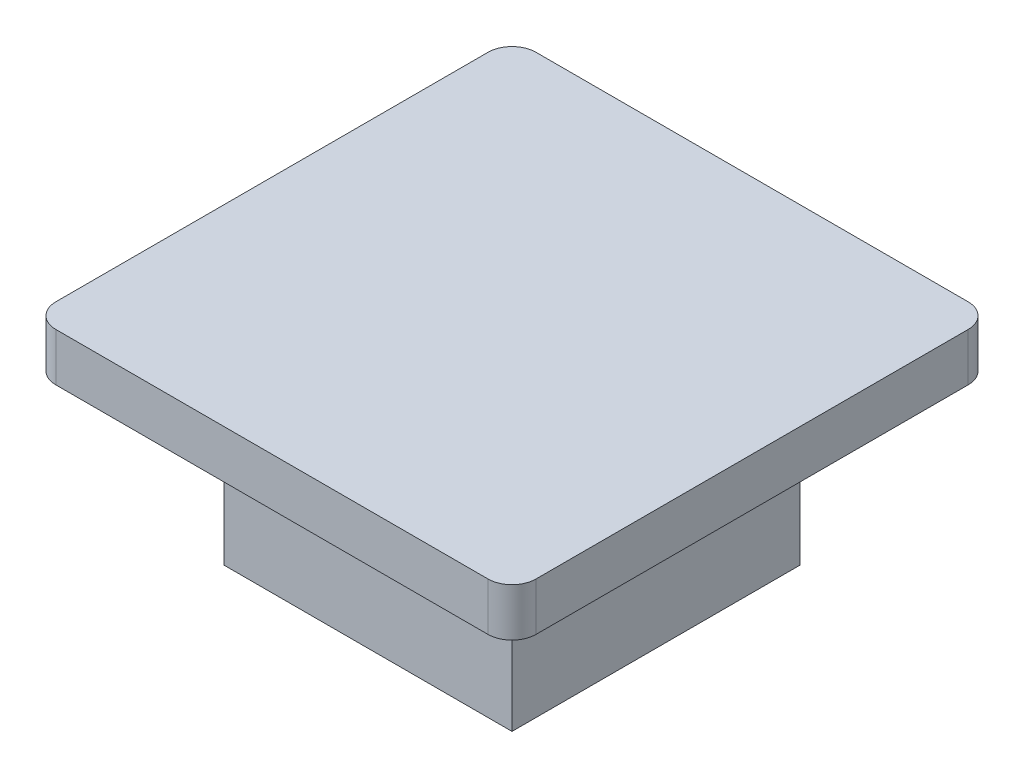
SolidWorks part; units mm, degrees
ref_plane "Front Plane" through (0, 0, 0) normal (0, 0, 1) x (1, 0, 0)
ref_plane "Top Plane" through (0, 0, 0) normal (0, 1, 0) x (1, 0, 0)
ref_plane "Right Plane" through (0, 0, 0) normal (1, 0, 0) x (0, 0, -1)
sketch "Sketch1" plane through (0, 0, 0) normal (0, 1, 0) x (1, 0, 0)
  line L1 (-100, -100) -> (100, -100)
  line L2 (-100, -100) -> (-100, 100)
  line L3 (-100, 100) -> (100, 100)
  line L4 (100, -100) -> (100, 100)
  line L5 (-100, -100) -> (100, 100) construction
  line L6 (-100, 100) -> (100, -100) construction
  point P0 (0, 0)
  dimension "D1" = 200
  dimension "D2" = 200
extrude "Boss-Extrude1" add sketch "Sketch1" along normal blind 20
sketch "Sketch3" plane through (0, 0, 0) normal (0, -1, 0) x (1, 0, 0)
  line L6 (-60, -60) -> (60, -60)
  line L7 (-60, -60) -> (-60, 60)
  line L8 (-60, 60) -> (60, 60)
  line L9 (60, -60) -> (60, 60)
  line L10 (-60, -60) -> (60, 60) construction
  line L11 (-60, 60) -> (60, -60) construction
  point P0 (0, 0)
  dimension "D1" = 120
  dimension "D2" = 120
extrude "Boss-Extrude2" add sketch "Sketch3" along normal blind 70
sketch "Sketch4" plane through (0, -70, 0) normal (0, -1, 0) x (1, 0, 0)
  line L0 (-80, 0) -> (117.0668, 0) construction
  line L2 (3.6479, 28.9379) -> (30.9916, 10.335)
  line L3 (3.6479, -28.9379) -> (30.9916, -10.335)
  arc A0 (30.9916, -10.335) -> (30.9916, 10.335) centre (23.9604, 0) ccw
  arc A1 (3.6479, 28.9379) -> (3.6479, -28.9379) centre (-16.0396, 0) ccw
  dimension "D2" = 25
  dimension "D3" = 35
  dimension "D1" = 40
extrude "Cut-Extrude1" cut sketch "Sketch4" against normal blind 20
sketch "Sketch5" plane through (0, -50, 0) normal (0, -1, 0) x (1, 0, 0)
  circle A0 centre (-16.0396, 0) radius 16
  circle A1 centre (23.9604, 0) radius 11
  dimension "D1" = 32
  dimension "D2" = 22
extrude "Cut-Extrude2" cut sketch "Sketch5" against normal blind 10
fillet "Fillet1" radius 10 4 edges at (-100, 10, -100) (-100, 10, 100) (100, 10, 100) (100, 10, -100)
fillet "Fillet4" radius 10 4 edges at (0, 0, 60) (60, 0, 0) (-60, 0, 0) (0, 0, -60)
